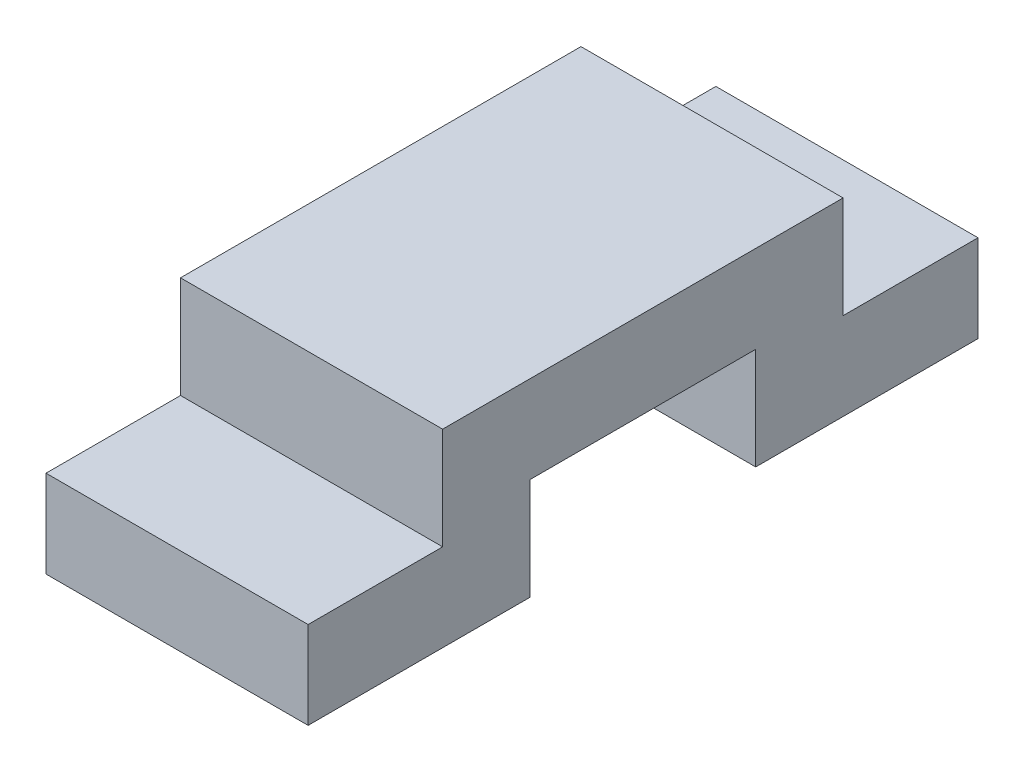
SolidWorks part; units mm, degrees
ref_plane "Front Plane" through (0, 0, 0) normal (0, 0, 1) x (1, 0, 0)
ref_plane "Top Plane" through (0, 0, 0) normal (0, 1, 0) x (1, 0, 0)
ref_plane "Right Plane" through (0, 0, 0) normal (1, 0, 0) x (0, 0, -1)
sketch "Sketch1" plane through (0, 0, 0) normal (0, 1, 0) x (1, 0, 0)
  line L1 (0, 0.2212) -> (9, 0.2212)
  line L2 (0, 0.2212) -> (0, 23.2212)
  line L3 (0, 23.2212) -> (9, 23.2212)
  line L4 (9, 0.2212) -> (9, 23.2212)
  dimension "D1" = 9
  dimension "D2" = 23
extrude "Boss-Extrude1" add sketch "Sketch1" along normal blind 15
sketch "Sketch2" plane through (9, 0, 0) normal (1, 0, 0) x (0, 0, -1)
  line L0 (23.2212, 0) -> (0.2212, 0) construction
  line L1 (7.8396, 3.5) -> (15.5896, 3.5)
  line L2 (7.8396, 3.5) -> (7.8396, 0)
  line L3 (7.8396, 0) -> (15.5896, 0)
  line L4 (8.0896, 3.25) -> (8.0896, -99.75)
  line L5 (8.0896, -99.75) -> (15.3396, -99.75)
  line L6 (15.3396, -99.75) -> (15.3396, 3.25)
  line L7 (15.3396, 3.25) -> (8.0896, 3.25)
  line L8 (8.0896, 3.25) -> (8.0896, -99.75)
  line L9 (8.0896, -99.75) -> (15.3396, -99.75)
  line L10 (15.3396, -99.75) -> (15.3396, 3.25)
  line L11 (15.3396, 3.25) -> (8.0896, 3.25)
  line L12 (15.5896, 3.5) -> (15.5896, 0)
  line L13 (0.2212, 0) -> (23.2212, 0) construction
  line L14 (4.8396, 0) -> (18.5896, 0)
  line L15 (4.8396, 0) -> (4.8396, 6.5)
  line L16 (4.8396, 6.5) -> (18.5896, 6.5)
  line L17 (18.5896, 0) -> (18.5896, 6.5)
  line L22 (0.2212, 3) -> (23.2212, 3)
  line L23 (0.2212, 15) -> (0.2212, 0) construction
  line L24 (23.2212, 15) -> (23.2212, 0) construction
  line M12 (23.2212, 0) -> (23.2212, 15)
  line M13 (23.2212, 15) -> (0.2212, 15)
  line M14 (0.2212, 15) -> (0.2212, 0)
  dimension "D2" = 0.25
  dimension "D3" = 0.25
  dimension "D4" = 0.25
  dimension "D5" = 3
  dimension "D6" = 3
  dimension "D7" = 3
  dimension "D8" = 3
  dimension "D1" = 0
extrude "Cut-Extrude1" cut sketch "Sketch2" against normal blind 15 contours L22 L15 L16 L17 M14 M12 M13 | L1 L12 L3 L2
sketch "Sketch3" plane through (0, 3, 0) normal (0, 1, 0) x (1, 0, 0)
  line L0 (4.5, 0.2212) -> (4.5, 23.2212) construction
  line L1 (0, 0.2212) -> (9, 0.2212) construction
  line L2 (0, 23.2212) -> (9, 23.2212) construction
  line L3 (0, 20.9054) -> (9, 20.9054) construction
  line L4 (0, 18.5896) -> (0, 23.2212) construction
  line L5 (9, 18.5896) -> (9, 23.2212) construction
  line L6 (0, 2.5304) -> (9, 2.5304) construction
  line L7 (0, 0.2212) -> (0, 4.8396) construction
  line L8 (9, 0.2212) -> (9, 4.8396) construction
  point P18 (4.5, 2.5304)
  point P19 (4.5, 20.9054)
equation "\"D1@Sketch1\"=\"bracket width@scotch-yoke - assembly.Assembly\""
equation "\"D2@Sketch1\"=\"carriage lip width@scotch-yoke - assembly.Assembly\"*2+\"carriage width@scotch-yoke - assembly.Assembly\""
equation "\"D5@Sketch2\"=\"bracket thickness@scotch-yoke - assembly.Assembly\""
equation "\"D6@Sketch2\"=\"bracket thickness@scotch-yoke - assembly.Assembly\""
equation "\"D7@Sketch2\"=\"bracket thickness@scotch-yoke - assembly.Assembly\""
equation "\"D8@Sketch2\"=\"bracket thickness@scotch-yoke - assembly.Assembly\""
